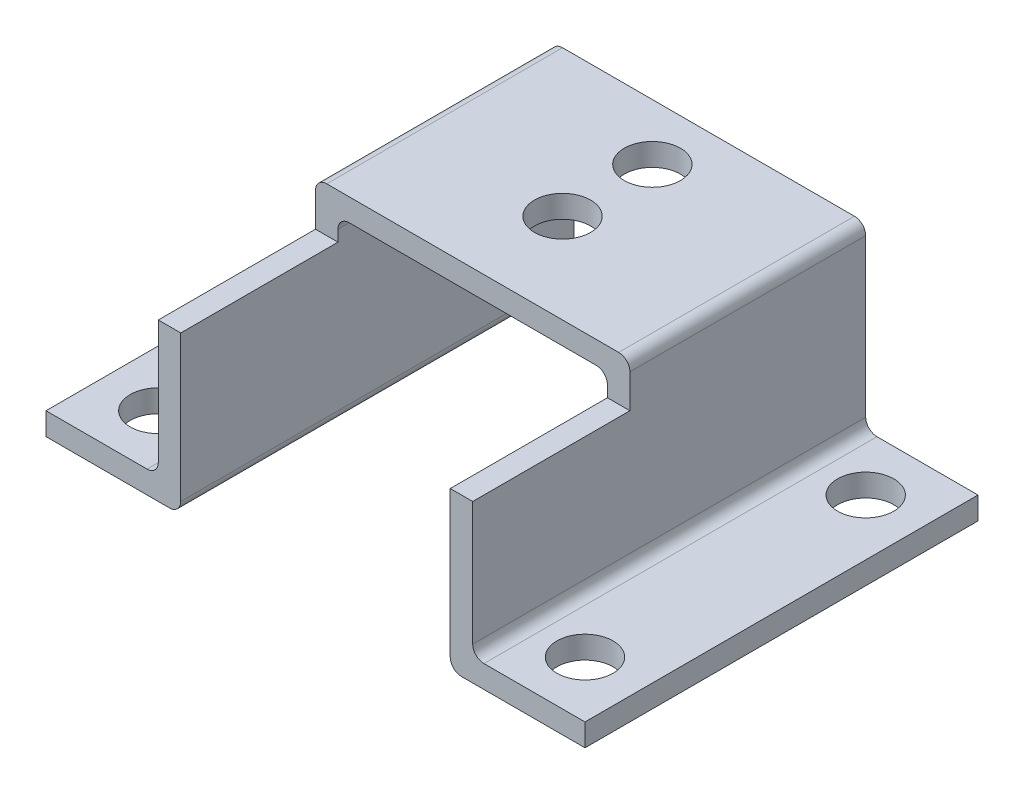
SolidWorks part; units mm, degrees
ref_plane "Front Plane" through (0, 0, 0) normal (0, 0, 1) x (1, 0, 0)
ref_plane "Top Plane" through (0, 0, 0) normal (0, 1, 0) x (1, 0, 0)
ref_plane "Right Plane" through (0, 0, 0) normal (1, 0, 0) x (0, 0, -1)
sketch "Sketch1" plane through (0, 0, 0) normal (0, 0, 1) x (1, 0, 0)
  line L0 (-24, 0) -> (-15, 0)
  line L1 (-14, 1) -> (-14, 15)
  line L2 (-13, 16) -> (13, 16)
  line L4 (11, 14) -> (-11, 14)
  line L5 (-12, 13) -> (-12, -1)
  line L6 (-13, -2) -> (-24, -2)
  line L7 (-24, -2) -> (-24, 0)
  line L8 (0, 34.4276) -> (0, 16) construction
  line L9 (24, -2) -> (24, 0)
  line L10 (13, -2) -> (24, -2)
  line L11 (12, 13) -> (12, -1)
  line L12 (14, 1) -> (14, 15)
  line L13 (24, 0) -> (15, 0)
  line L14 (0, 14) -> (0, -18.3724) construction
  arc A0 (-14, 15) -> (-13, 16) centre (-13, 15) cw
  arc A1 (-11, 14) -> (-12, 13) centre (-11, 13) ccw
  arc A2 (-12, -1) -> (-13, -2) centre (-13, -1) cw
  arc A3 (-15, 0) -> (-14, 1) centre (-15, 1) ccw
  arc A4 (13, -2) -> (12, -1) centre (13, -1) cw
  arc A5 (14, 1) -> (15, 0) centre (15, 1) ccw
  arc A6 (14, 15) -> (13, 16) centre (13, 15) ccw
  arc A7 (12, 13) -> (11, 14) centre (11, 13) ccw
  point P17 (-18.5, -2)
  point P20 (-14, 16)
  point P23 (-12, 14)
  point P26 (-12, -2)
  point P29 (-14, 0)
  point P32 (12, -2)
  point P35 (14, 0)
  point P38 (14, 16)
  point P41 (12, 14)
  dimension "D7" = 1
  dimension "D8" = 1
  dimension "D1" = 24
  dimension "D2" = 48
  dimension "D3" = 16
  dimension "D4" = 2
  dimension "D5" = 2
  dimension "D6" = 2
extrude "Boss-Extrude1" add sketch "Sketch1" along normal blind 35
sketch "Sketch2" plane through (14, 0, 0) normal (1, 0, 0) x (0, 0, -1)
  line L0 (-35, 16) -> (-35, 15) construction
  line L1 (-35, 16) -> (-21, 16)
  line L2 (-35, 16) -> (-35, 12)
  line L3 (-35, 12) -> (-21, 12)
  line L4 (-21, 16) -> (-21, 12)
  point P6 (0, 0)
  dimension "D1" = 14
  dimension "D2" = 4
extrude "Cut-Extrude1" cut sketch "Sketch2" against normal through all
sketch "Sketch3" plane through (0, 0, 0) normal (0, 1, 0) x (1, 0, 0)
  line L0 (0, 7.5576) -> (0, -35.5672) construction
  line L1 (-15, 0) -> (-24, 0) construction
  line L2 (-15, -35) -> (-24, -35) construction
  line L3 (-13, -21) -> (13, -21) construction
  circle A0 centre (-19, -5) radius 2.5
  circle A1 centre (-19, -30) radius 2.5
  circle A2 centre (19, -30) radius 2.5
  circle A3 centre (19, -5) radius 2.5
  circle A4 centre (0, -13) radius 2.5
  circle A5 centre (0, -5) radius 2.5
  dimension "D1" = 5
  dimension "D8" = 5
  dimension "D2" = 5
  dimension "D3" = 5
  dimension "D4" = 25
  dimension "D5" = 38
  dimension "D6" = 8
  dimension "D7" = 16
extrude "Cut-Extrude2" cut sketch "Sketch3" against normal through all both and the other way through all
